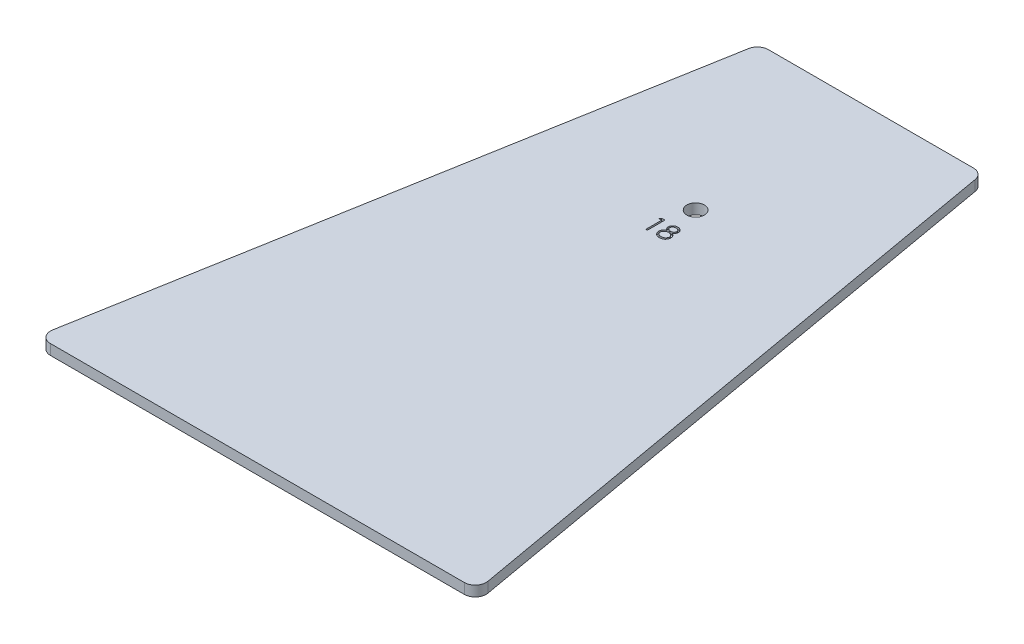
SolidWorks part; units mm, degrees
material "Acrylic (Medium-high impact)"
ref_plane "Front Plane" through (0, 0, 0) normal (0, 0, 1) x (1, 0, 0)
ref_plane "Top Plane" through (0, 0, 0) normal (0, 1, 0) x (1, 0, 0)
ref_plane "Right Plane" through (0, 0, 0) normal (1, 0, 0) x (0, 0, -1)
sketch "Sketch1" plane through (0, 0, 0) normal (0, 1, 0) x (1, 0, 0)
  line L0 (0, 0) -> (0, -355.6) construction
  line L1 (-64.77, 0) -> (64.77, 0)
  line L2 (64.77, 0) -> (127.4719, -355.6)
  line L3 (127.4719, -355.6) -> (-127.4719, -355.6)
  line L4 (-64.77, 0) -> (-127.4719, -355.6)
  dimension "D1" = 355.6
  dimension "D2" = 20
  dimension "D3" = 129.54
extrude "Boss-Extrude1" add sketch "Sketch1" along normal blind 5.9944
sketch "Sketch2" plane through (0, 5.9944, 0) normal (0, 1, 0) x (1, 0, 0)
  line L0 (0, 0) -> (0, -101.6) construction
  line L1 (64.77, 0) -> (-64.77, 0) construction
  circle A0 centre (0, -101.6) radius 5.08
  dimension "D1" = 10.16
  dimension "D2" = 101.6
extrude "Cut-Extrude1" cut sketch "Sketch2" against normal through all
sketch "Sketch3" plane through (0, 5.9944, 0) normal (0, 1, 0) x (1, 0, 0)
  line L0 (0, -101.6) -> (0, -114.3) construction
  line L2 (8.255, -125.73) -> (8.255, -114.3) construction
  line L3 (8.255, -125.73) -> (-8.255, -125.73) construction
  line L4 (8.255, -114.3) -> (-8.255, -114.3) construction
  line L5 (-8.255, -125.73) -> (-8.255, -114.3) construction
  line L6 (8.255, -125.73) -> (-8.255, -114.3) construction
  line L7 (8.255, -114.3) -> (-8.255, -125.73) construction
  text T0 "18" font "Century Gothic" height 10.16
  point P4 (0, -120.015)
  dimension "D1" = 11.43
  dimension "D2" = 16.51
  dimension "D3" = 12.7
extrude "Cut-Extrude2" cut sketch "Sketch3" against normal blind 1.27
fillet "Fillet1" radius 6.35 4 edges at (127.4719, 2.9972, 355.6) (-127.4719, 2.9972, 355.6) (64.77, 2.9972, 0) (-64.77, 2.9972, 0)
